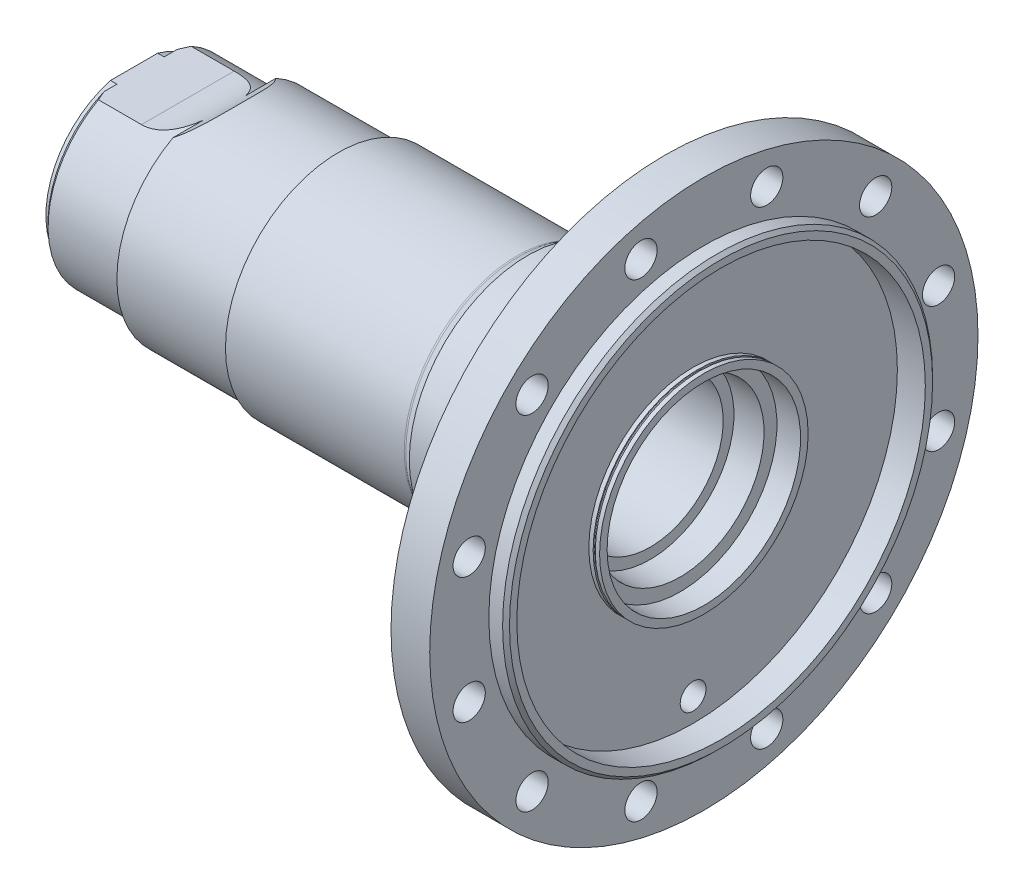
SolidWorks part; units mm, degrees
ref_plane "Спереди" through (0, 0, 0) normal (0, 0, 1) x (1, 0, 0)
ref_plane "Сверху" through (0, 0, 0) normal (0, 1, 0) x (1, 0, 0)
ref_plane "Справа" through (0, 0, 0) normal (1, 0, 0) x (0, 0, -1)
sketch "Эскиз1" plane through (0, 0, 0) normal (0, 0, 1) x (1, 0, 0)
  line L0 (0, 0) -> (273, 0)
  line L1 (0, 0) -> (0, 41)
  line L2 (0, 41) -> (3, 41)
  line L3 (3, 41) -> (3, 43)
  line L4 (3, 43) -> (5, 45)
  line L5 (5, 45) -> (42, 45)
  line L6 (42, 45) -> (42, 50)
  line L7 (42, 50) -> (95, 50)
  line L8 (95, 50) -> (95, 52.5)
  line L9 (95, 52.5) -> (178.134, 52.5)
  line L10 (179.134, 52.7679) -> (183, 55)
  line L11 (183, 55) -> (213, 55)
  line L12 (215, 57) -> (215, 60.7679)
  line L13 (215, 60.7679) -> (218, 62.5)
  line L14 (218, 62.5) -> (237, 62.5)
  line L15 (239, 64.5) -> (239, 65.5)
  line L16 (239, 65.5) -> (240.4142, 66.9142)
  line L17 (241, 68.3284) -> (241, 78)
  line L18 (241, 78) -> (244.4142, 81.4142)
  line L19 (245, 82.8284) -> (245, 92)
  line L20 (245, 92) -> (246.4142, 93.4142)
  line L21 (247, 94.8284) -> (247, 127.5)
  line L22 (247, 127.5) -> (265, 127.5)
  line L23 (265, 127.5) -> (265, 100)
  line L24 (265, 100) -> (271.4, 100)
  line L25 (271.4, 100) -> (273, 98.4)
  line L26 (273, 98.4) -> (273, 0)
  arc A0 (178.134, 52.5) -> (179.134, 52.7679) centre (178.134, 54.5) ccw
  arc A1 (213, 55) -> (215, 57) centre (213, 57) ccw
  arc A2 (237, 62.5) -> (239, 64.5) centre (237, 64.5) ccw
  arc A3 (240.4142, 66.9142) -> (241, 68.3284) centre (239, 68.3284) ccw
  arc A4 (244.4142, 81.4142) -> (245, 82.8284) centre (243, 82.8284) ccw
  arc A5 (246.4142, 93.4142) -> (247, 94.8284) centre (245, 94.8284) ccw
revolve "Повернуть1" add sketch "Эскиз1" angle 360 about L0
sketch "Эскиз2" plane through (0, 0, 0) normal (0, 0, 1) x (1, 0, 0)
  line L0 (0, 0) -> (273, 0)
  line L1 (0, 0) -> (0, 32.7321)
  line L2 (0, 32.7321) -> (3, 31)
  line L3 (3, 31) -> (203.5, 31)
  line L4 (203.5, 31) -> (203.5, 34)
  line L5 (203.5, 34) -> (240, 34)
  line L6 (240, 34) -> (240, 39)
  line L7 (240, 39) -> (254, 39)
  line L8 (254, 39) -> (254, 45)
  line L9 (254, 45) -> (265, 45)
  line L10 (265, 45) -> (265, 95)
  line L11 (265, 95) -> (273, 95)
  line L12 (273, 95) -> (273, 0)
revolve "Вырез-Повернуть1" cut sketch "Эскиз2" angle 360 about L0
sketch "Эскиз3" plane through (0, 0, 0) normal (0, 0, 1) x (1, 0, 0)
  line L0 (0, 0) -> (273, 0) construction
  line L1 (260, 48.5) -> (262, 48.5)
  line L2 (262, 48.5) -> (262, 95)
  line L3 (262, 95) -> (260, 95)
  line L4 (260, 95) -> (260, 48.5)
revolve "Rear_recess_left" cut sketch "Эскиз3" angle 360 about L0
sketch "Эскиз4" plane through (0, 0, 0) normal (0, 0, 1) x (1, 0, 0)
  line L0 (0, 0) -> (273, 0) construction
  line L1 (263, 48) -> (263, 95)
  line L2 (263, 95) -> (262, 95)
  line L3 (262, 95) -> (262, 48)
  arc A0 (262, 48) -> (262.5, 47.5) centre (262.5, 48) ccw
  arc A1 (262.5, 47.5) -> (263, 48) centre (262.5, 48) ccw
revolve "Collar_groove_nominal" cut sketch "Эскиз4" angle 360 about L0
sketch "Эскиз5" plane through (0, 0, 0) normal (0, 0, 1) x (1, 0, 0)
  line L0 (0, 0) -> (273, 0) construction
  line L1 (263, 48.5) -> (265, 48.5)
  line L2 (265, 48.5) -> (265, 95)
  line L3 (265, 95) -> (263, 95)
  line L4 (263, 95) -> (263, 48.5)
revolve "Rear_recess_lip" cut sketch "Эскиз5" angle 360 about L0
sketch "Эскиз6" plane through (0, 0, 0) normal (1, 0, 0) x (0, 0, -1)
  circle A0 centre (109.1496, 29.2466) radius 7.5
extrude "Вырез-Вытянуть1" cut sketch "Эскиз6" along normal through all
sketch "Эскиз7" plane through (0, 0, 0) normal (1, 0, 0) x (0, 0, -1)
  circle A0 centre (79.9031, 79.9031) radius 7.5
extrude "Вырез-Вытянуть2" cut sketch "Эскиз7" along normal through all
sketch "Эскиз8" plane through (0, 0, 0) normal (1, 0, 0) x (0, 0, -1)
  circle A0 centre (29.2466, 109.1496) radius 7.5
extrude "Вырез-Вытянуть3" cut sketch "Эскиз8" along normal through all
sketch "Эскиз9" plane through (0, 0, 0) normal (1, 0, 0) x (0, 0, -1)
  circle A0 centre (-29.2466, 109.1496) radius 7.5
extrude "Вырез-Вытянуть4" cut sketch "Эскиз9" along normal through all
sketch "Эскиз10" plane through (0, 0, 0) normal (1, 0, 0) x (0, 0, -1)
  circle A0 centre (-79.9031, 79.9031) radius 7.5
extrude "Вырез-Вытянуть5" cut sketch "Эскиз10" along normal through all
sketch "Эскиз11" plane through (0, 0, 0) normal (1, 0, 0) x (0, 0, -1)
  circle A0 centre (-109.1496, 29.2466) radius 7.5
extrude "Вырез-Вытянуть6" cut sketch "Эскиз11" along normal through all
sketch "Эскиз12" plane through (0, 0, 0) normal (1, 0, 0) x (0, 0, -1)
  circle A0 centre (-109.1496, -29.2466) radius 7.5
extrude "Вырез-Вытянуть7" cut sketch "Эскиз12" along normal through all
sketch "Эскиз13" plane through (0, 0, 0) normal (1, 0, 0) x (0, 0, -1)
  circle A0 centre (-79.9031, -79.9031) radius 7.5
extrude "Вырез-Вытянуть8" cut sketch "Эскиз13" along normal through all
sketch "Эскиз14" plane through (0, 0, 0) normal (1, 0, 0) x (0, 0, -1)
  circle A0 centre (-29.2466, -109.1496) radius 7.5
extrude "Вырез-Вытянуть9" cut sketch "Эскиз14" along normal through all
sketch "Эскиз15" plane through (0, 0, 0) normal (1, 0, 0) x (0, 0, -1)
  circle A0 centre (29.2466, -109.1496) radius 7.5
extrude "Вырез-Вытянуть10" cut sketch "Эскиз15" along normal through all
sketch "Эскиз16" plane through (0, 0, 0) normal (1, 0, 0) x (0, 0, -1)
  circle A0 centre (79.9031, -79.9031) radius 7.5
extrude "Вырез-Вытянуть11" cut sketch "Эскиз16" along normal through all
sketch "Эскиз17" plane through (0, 0, 0) normal (1, 0, 0) x (0, 0, -1)
  circle A0 centre (109.1496, -29.2466) radius 7.5
extrude "Вырез-Вытянуть12" cut sketch "Эскиз17" along normal through all
sketch "Эскиз18" plane through (0, 0, 0) normal (1, 0, 0) x (0, 0, -1)
  circle A0 centre (0, -84) radius 6
extrude "Вырез-Вытянуть13" cut sketch "Эскиз18" along normal through all
sketch "Эскиз19" plane through (0, 0, 0) normal (0, 0, 1) x (1, 0, 0)
  line L0 (-1, 39.5) -> (25, 39.5)
  line L1 (60, 74.5) -> (60, 150)
  line L2 (60, 150) -> (-1, 150)
  line L3 (-1, 150) -> (-1, 39.5)
  arc A0 (25, 39.5) -> (60, 74.5) centre (25, 74.5) ccw
extrude "Left_flat_84_5_R35" cut sketch "Эскиз19" against normal through all and the other way through all
sketch "Эскиз20" plane through (0, 0, 0) normal (0, 0, 1) x (1, 0, 0)
  line L0 (-1, -25) -> (3, -25)
  line L1 (3, -25) -> (3, -100)
  line L2 (3, -100) -> (-1, -100)
  line L3 (-1, -100) -> (-1, -25)
extrude "Left_end_bottom_20" cut sketch "Эскиз20" against normal through all and the other way through all
